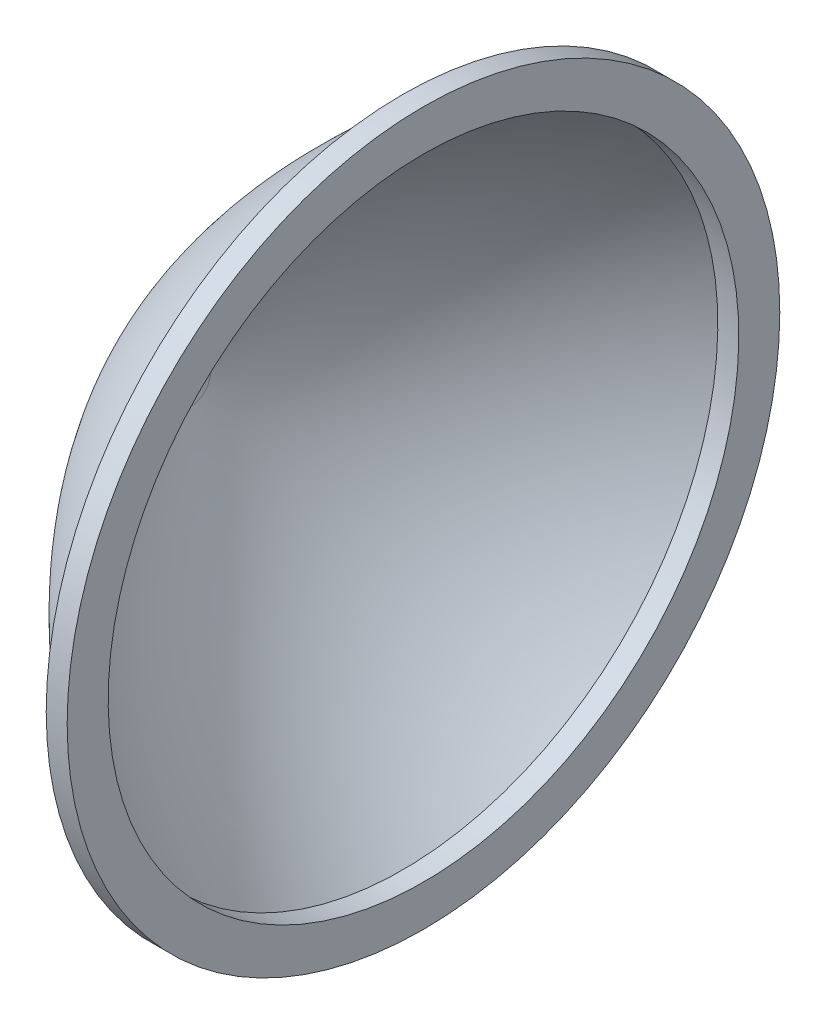
SolidWorks part; units mm, degrees
ref_plane "Plan de face" through (0, 0, 0) normal (0, 0, 1) x (1, 0, 0)
ref_plane "Plan de dessus" through (0, 0, 0) normal (0, 1, 0) x (1, 0, 0)
ref_plane "Plan de droite" through (0, 0, 0) normal (1, 0, 0) x (0, 0, -1)
sketch "Esquisse1" plane through (0, 0, 0) normal (0, 0, 1) x (1, 0, 0)
  line L6 (-45.642, 0) -> (-50, 0)
  line L8 (0, 68) -> (0, 60.1756)
  line L11 (-4, 60.1756) -> (0, 60.1756)
  line L16 (-4, 65.1715) -> (-4, 68)
  line L17 (-4, 68) -> (0, 68)
  spline S0 degree 2 poles (-4, 65.1715) (-38.7618, 39.7186) (-50, 0) knots 0.053439 0.053439 0.053439 1 1 1
  spline S2 degree 2 poles (-4, 60.1756) (-15.0938, 51.6838) (-29.1935, 35.0066) (-40.4181, 16.6205) (-44.5915, 4) knots 0.086931 0.086931 0.086931 0.405563 0.617984 0.936615 0.936615 0.936615
  spline S3 degree 1 poles (-44.5915, 4) (-45.642, 0) knots 0 0 1 1
revolve "Révolution4" add sketch "Esquisse1" angle 360 about L6
